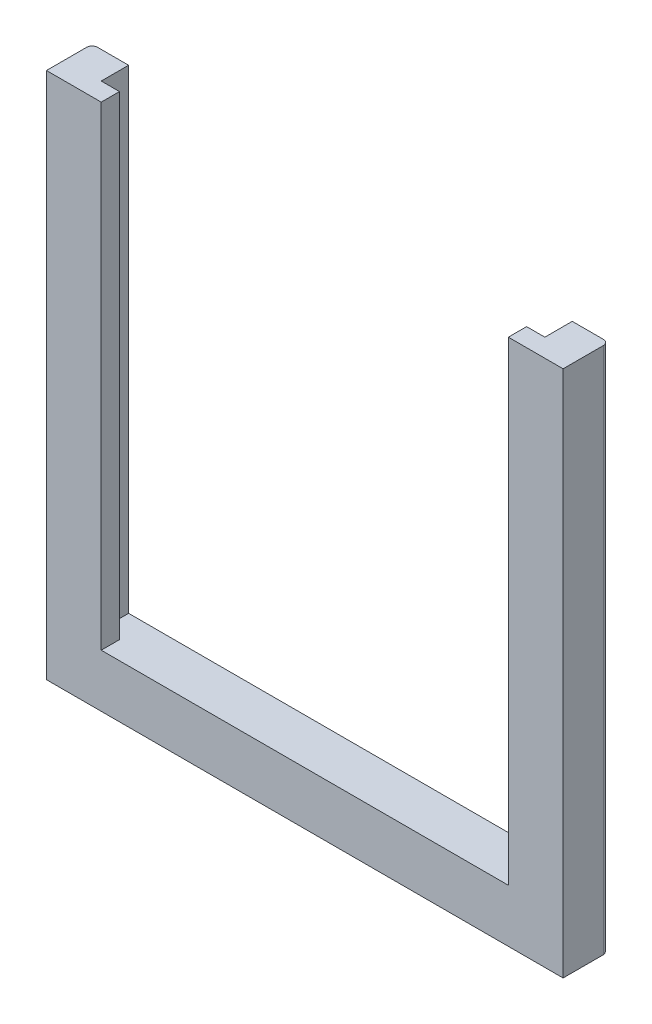
SolidWorks part; units mm, degrees
material "ABS"
ref_plane "Plano frontal" through (0, 0, 0) normal (0, 0, 1) x (1, 0, 0)
ref_plane "Plano superior" through (0, 0, 0) normal (0, 1, 0) x (1, 0, 0)
ref_plane "Plano direito" through (0, 0, 0) normal (1, 0, 0) x (0, 0, -1)
sketch "Esboço1" plane through (0, 0, 0) normal (0, 0, 1) x (1, 0, 0)
  line L1 (0, 0) -> (28.3, 0)
  line L2 (0, 0) -> (0, 28.9)
  line L3 (0, 28.9) -> (28.3, 28.9)
  line L4 (28.3, 0) -> (28.3, 28.9)
  line L6 (2.7482, 28.9) -> (0.3, 28.9) construction
  dimension "D1" = 28.3
extrude "Ressalto-extrusão1" add sketch "Esboço1" along normal up to vertex (2.5 mm away)
fillet "Filete1" radius 0.3 3 edges at (14.15, 0, 0) (28.3, 14.45, 0) (0, 14.45, 0)
sketch "Esboço2" plane through (0, 28.9, 0) normal (0, 1, 0) x (1, 0, 0)
  line L0 (28, 0) -> (0.3, 0) construction
  line L1 (26.3, 0) -> (2, 0)
  line L2 (26.3, 0) -> (26.3, -1.5)
  line L3 (26.3, -1.5) -> (25.3, -1.5)
  line L4 (2, 0) -> (2, -1.5)
  line L5 (25.3, -1.5) -> (25.3, -2.5)
  line L6 (28.3, -2.5) -> (0, -2.5) construction
  line L7 (25.3, -2.5) -> (3, -2.5)
  line L8 (3, -2.5) -> (3, -1.5)
  line L9 (3, -1.5) -> (2, -1.5)
  line L10 (0, -2.5) -> (0, -0.3) construction
  line L11 (28.3, -2.5) -> (28.3, -0.3) construction
  dimension "D1" = 2
  dimension "D2" = 2
  dimension "D3" = 1
  dimension "D4" = 1
  dimension "D5" = 1.5
extrude "Corte-extrusão1" cut sketch "Esboço2" against normal blind 26
